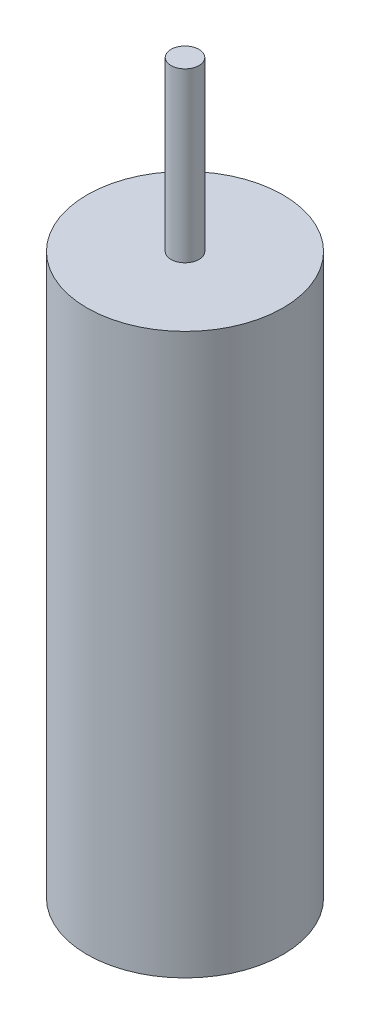
SolidWorks part; units mm, degrees
material "AISI 304"
ref_plane "Front" through (0, 0, 0) normal (0, 0, 1) x (1, 0, 0)
ref_plane "Top" through (0, 0, 0) normal (0, 1, 0) x (1, 0, 0)
ref_plane "Right" through (0, 0, 0) normal (1, 0, 0) x (0, 0, -1)
sketch "草图1" plane through (0, 0, 0) normal (0, 1, 0) x (1, 0, 0)
  circle A0 centre (0, 0) radius 3.5
  dimension "D1" = 7
extrude "凸台-拉伸1" add sketch "草图1" along normal blind 20
sketch "草图2" plane through (0, 20, 0) normal (0, 1, 0) x (1, 0, 0)
  circle A0 centre (0, 0) radius 0.5
  dimension "D1" = 1
extrude "凸台-拉伸2" add sketch "草图2" along normal blind 6
